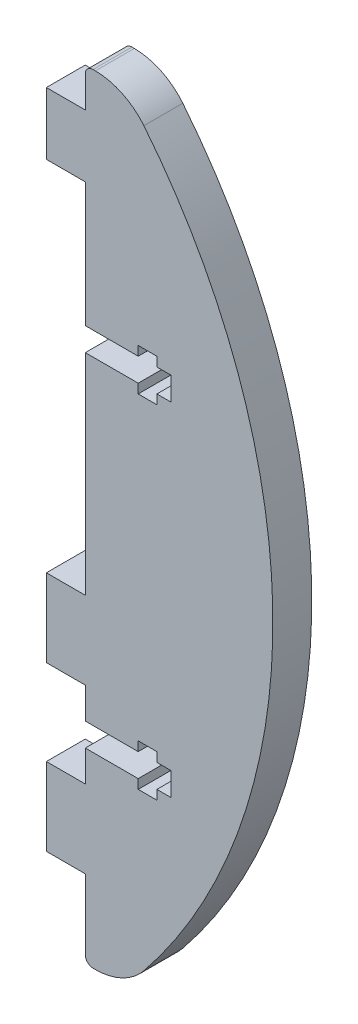
SolidWorks part; units mm, degrees
ref_plane "Plano frontal" through (0, 0, 0) normal (0, 0, 1) x (1, 0, 0)
ref_plane "Plano superior" through (0, 0, 0) normal (0, 1, 0) x (1, 0, 0)
ref_plane "Plano direito" through (0, 0, 0) normal (1, 0, 0) x (0, 0, -1)
sketch "Model" plane through (0, 0, 0) normal (0, 0, 1) x (1, 0, 0)
  line L0 (-182, 45) -> (-182, 54)
  line L1 (-182, 54) -> (-187, 54)
  line L2 (-187, 54) -> (-187, 64)
  line L3 (-187, 64) -> (-182, 64)
  line L4 (-182, 64) -> (-182, 68)
  line L5 (-182, 68) -> (-175.2, 68)
  line L6 (-175.2, 68) -> (-175.2, 66.8)
  line L7 (-175.2, 66.8) -> (-172.8, 66.8)
  line L8 (-172.8, 66.8) -> (-172.8, 68)
  line L9 (-172.8, 68) -> (-171, 68)
  line L10 (-171, 68) -> (-171, 71)
  line L11 (-171, 71) -> (-172.8, 71)
  line L12 (-172.8, 71) -> (-172.8, 72.2)
  line L13 (-172.8, 72.2) -> (-175.2, 72.2)
  line L14 (-175.2, 72.2) -> (-175.2, 71)
  line L15 (-175.2, 71) -> (-182, 71)
  line L16 (-182, 71) -> (-182, 75)
  line L17 (-182, 75) -> (-187, 75)
  line L18 (-187, 75) -> (-187, 85)
  line L19 (-187, 85) -> (-182, 85)
  line L20 (-182, 85) -> (-182, 112)
  line L21 (-182, 112) -> (-175.2, 112)
  line L22 (-175.2, 112) -> (-175.2, 110.8)
  line L23 (-175.2, 110.8) -> (-172.8, 110.8)
  line L24 (-172.8, 110.8) -> (-172.8, 112)
  line L25 (-172.8, 112) -> (-171, 112)
  line L26 (-171, 112) -> (-171, 115)
  line L27 (-171, 115) -> (-172.8, 115)
  line L28 (-172.8, 115) -> (-172.8, 116.2)
  line L29 (-172.8, 116.2) -> (-175.2, 116.2)
  line L30 (-175.2, 116.2) -> (-175.2, 115)
  line L31 (-175.2, 115) -> (-182, 115)
  line L32 (-182, 115) -> (-182, 131)
  line L33 (-182, 131) -> (-187, 131)
  line L34 (-187, 131) -> (-187, 139)
  line L35 (-187, 139) -> (-182, 139)
  line L36 (-182, 139) -> (-182, 143)
  line L37 (-181, 144) -> (-180.6987, 144)
  line L38 (-180.6987, 44) -> (-181, 44)
  arc A0 (-182, 45) -> (-181, 44) centre (-181, 45) ccw
  arc A1 (-181, 144) -> (-182, 143) centre (-181, 143) ccw
  arc A2 (-174.4672, 141.0168) -> (-180.6987, 144) centre (-180.762, 135.8678) ccw
  arc A3 (-174.4672, 46.9832) -> (-174.4672, 141.0168) centre (-232.8686, 94) ccw
  arc A4 (-180.6987, 44) -> (-174.4672, 46.9832) centre (-180.7139, 52.0317) ccw
extrude "Ressalto-extrusão1" add sketch "Model" along normal blind 5
